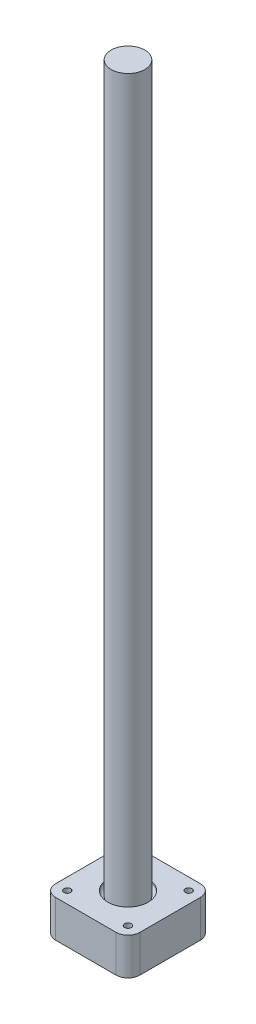
SolidWorks part; units mm, degrees
ref_plane "Front Plane" through (0, 0, 0) normal (0, 0, 1) x (1, 0, 0)
ref_plane "Top Plane" through (0, 0, 0) normal (0, 1, 0) x (1, 0, 0)
ref_plane "Right Plane" through (0, 0, 0) normal (1, 0, 0) x (0, 0, -1)
sketch "Sketch1" plane through (0, 0, 0) normal (0, 1, 0) x (1, 0, 0)
  line L0 (0, 0) -> (0, -50)
  line L1 (0, -50) -> (50, -50)
  line L2 (50, -50) -> (50, 0)
  line L3 (50, 0) -> (0, 0)
extrude "Boss-Extrude1" add sketch "Sketch1" along normal blind 22
fillet "Fillet1" radius 7 4 edges at (0, 11, 0) (50, 11, 0) (50, 11, 50) (0, 11, 50)
sketch "Sketch2" plane through (0, 22, 0) normal (0, 1, 0) x (1, 0, 0)
  circle A0 centre (7, -7) radius 2
  circle A1 centre (7, -43) radius 2
  circle A2 centre (43, -43) radius 2
  circle A3 centre (43, -7) radius 2
extrude "Cut-Extrude1" cut sketch "Sketch2" against normal blind 22
sketch "Sketch3" plane through (0, 22, 0) normal (0, 1, 0) x (1, 0, 0)
  circle A0 centre (25, -25) radius 12
extrude "Cut-Extrude2" cut sketch "Sketch3" against normal blind 3
fillet "Fillet2" radius 2 1 edges at (25, 19, 37)
sketch "Sketch4" plane through (0, 19, 0) normal (0, 1, 0) x (1, 0, 0)
  circle A0 centre (25, -25) radius 10
extrude "Boss-Extrude2" add sketch "Sketch4" along normal blind 430
